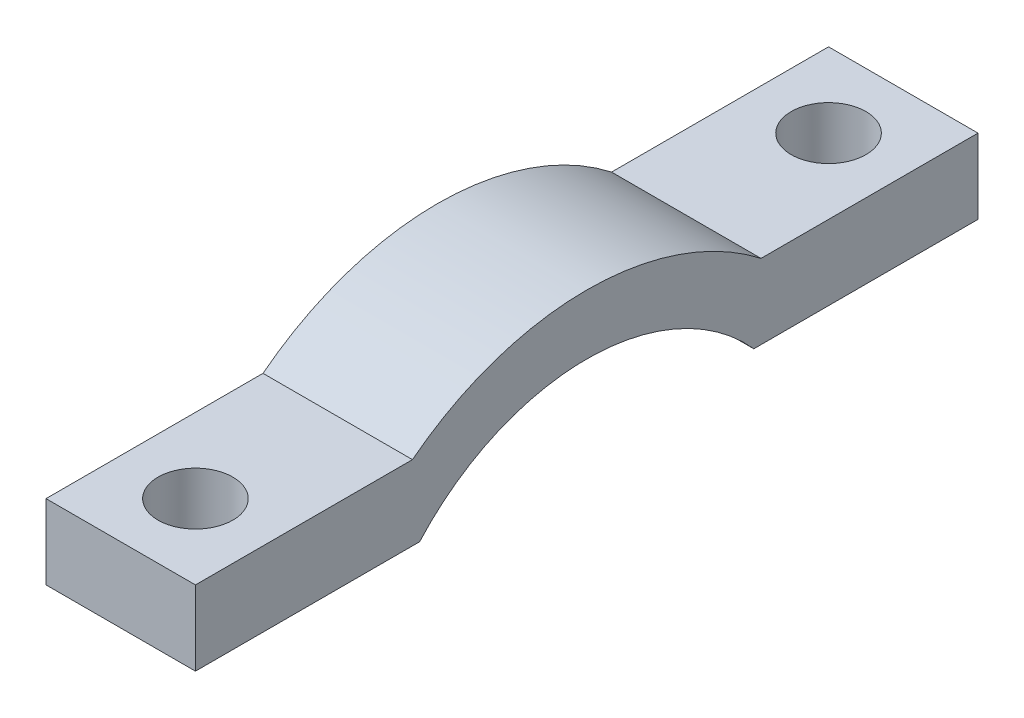
SolidWorks part; units mm, degrees
ref_plane "Plan de face" through (0, 0, 0) normal (0, 0, 1) x (1, 0, 0)
ref_plane "Plan de dessus" through (0, 0, 0) normal (0, 1, 0) x (1, 0, 0)
ref_plane "Plan de droite" through (0, 0, 0) normal (1, 0, 0) x (0, 0, -1)
sketch "Esquisse2" plane through (0, 0, 0) normal (1, 0, 0) x (0, 0, -1)
  line L0 (-16.7178, 10) -> (20.1552, 10) construction
  line L1 (-14.3614, 10) -> (-26.1803, 10)
  line L2 (-26.1803, 10) -> (-26.1803, 15)
  line L3 (-26.1803, 15) -> (-11.6619, 15)
  line L4 (14.3614, 10) -> (21.1803, 10)
  line L5 (26.1803, 15) -> (26.1803, 10)
  line L6 (26.1803, 15) -> (11.6619, 15)
  line L7 (26.1803, 10) -> (21.1803, 10)
  line L8 (-14.3614, 10) -> (-11.1803, 10)
  line L9 (11.1803, 10) -> (21.1803, 10)
  arc A0 (11.1803, 10) -> (-11.1803, 10) centre (0, 0) ccw
  arc A2 (11.6619, 15) -> (-11.6619, 15) centre (0, 0) ccw
  point P5 (-21.1803, 10)
  point P6 (21.1803, 10)
  point P7 (-11.1803, 10)
  point P8 (11.1803, 10)
  dimension "D1" = 30
  dimension "D3" = 10
  dimension "D5" = 5
  dimension "D7" = 4
  dimension "D2" = 10
  dimension "D4" = 10
  dimension "D6" = 5
  dimension "D8" = 5
  dimension "D9" = 5
extrude "BASE" add sketch "Esquisse2" along normal blind 10 contours L6 A2 L3 L2 L1 L8 A0 L9 L4 L7 L5
sketch "Esquisse5" plane through (0, 10, 0) normal (0, -1, 0) x (1, 0, 0)
  line L0 (5, 26.1803) -> (5, 11.1803) construction
  line L1 (10, 26.1803) -> (0, 26.1803) construction
  line L2 (10, 11.1803) -> (0, 11.1803) construction
  line L3 (-3.4429, 0) -> (13.3559, 0) construction
  circle A0 centre (5, 21.1803) radius 2.5
  circle A1 centre (5, -21.1803) radius 2.5
  dimension "D2" = 5
  dimension "D1" = 5
extrude "VIDE ACCES VIS" cut sketch "Esquisse5" against normal through all
